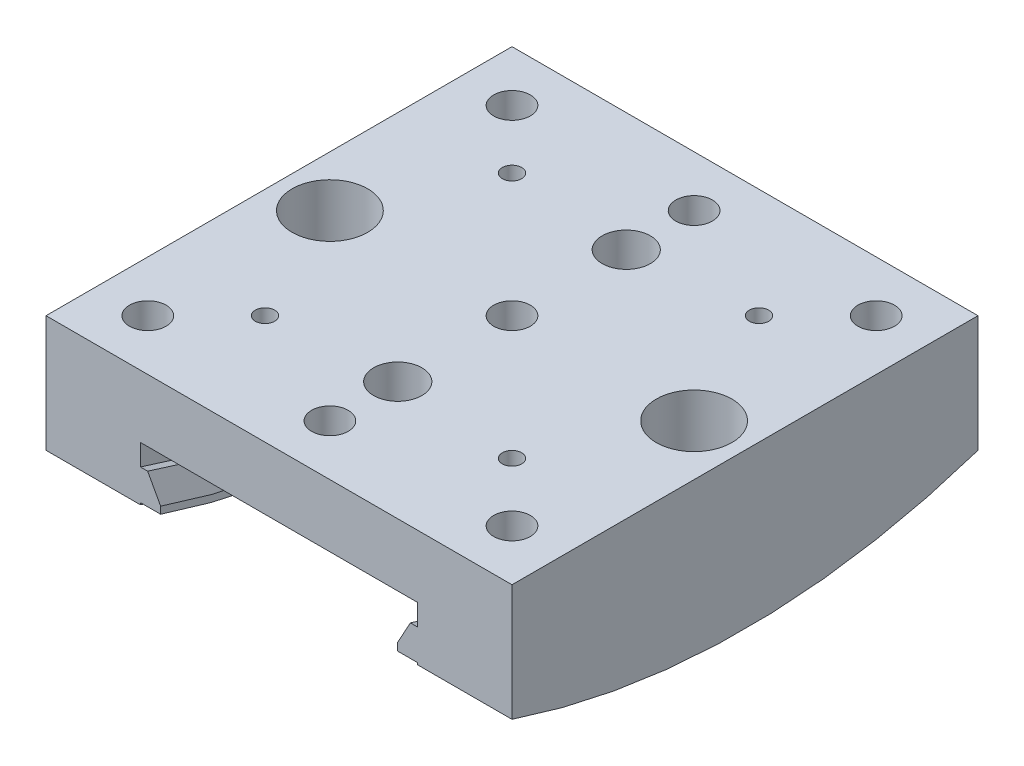
SolidWorks part; units mm, degrees
ref_plane "Ebene vorne" through (0, 0, 0) normal (0, 0, 1) x (1, 0, 0)
ref_plane "Ebene oben" through (0, 0, 0) normal (0, 1, 0) x (1, 0, 0)
ref_plane "Ebene rechts" through (0, 0, 0) normal (1, 0, 0) x (0, 0, -1)
sketch "Skizze1" plane through (0, 0, 0) normal (0, 0, 1) x (1, 0, 0)
  line L1 (-32.5, 15) -> (32.5, 15)
  line L2 (-32.5, 15) -> (-32.5, -15)
  line L3 (-32.5, -15) -> (32.5, -15)
  line L4 (32.5, 15) -> (32.5, -15)
  point P4 (0, 15)
  point P6 (-32.5, 0)
  dimension "D1" = 30
  dimension "D2" = 65
extrude "Aufsatz-Linear austragen1" add sketch "Skizze1" along normal blind 65
sketch "Skizze7" plane through (0, 0, 65) normal (0, 0, 1) x (1, 0, 0)
  line L0 (19.3305, 6.277) -> (-19.3305, 6.277)
  line L1 (-19.3305, 6.277) -> (-19.3305, 3.307)
  line L2 (-19.3305, 3.307) -> (-18.3215, 3.307)
  line L3 (-18.3215, 3.307) -> (-16.5095, -0.015)
  line L4 (-16.5095, -0.015) -> (-16.5095, -0.994)
  line L5 (-16.5095, -0.994) -> (-19.3305, -0.994)
  line L6 (-19.3305, -0.994) -> (-19.3305, -1.262)
  line L7 (-19.3305, -1.262) -> (19.3305, -1.262)
  line L9 (32.5, 15) -> (-32.5, 15) construction
  line L11 (19.3305, -0.994) -> (19.3305, -1.262)
  line L12 (16.5095, -0.994) -> (19.3305, -0.994)
  line L13 (16.5095, -0.015) -> (16.5095, -0.994)
  line L14 (18.3215, 3.307) -> (16.5095, -0.015)
  line L15 (19.3305, 3.307) -> (18.3215, 3.307)
  line L16 (19.3305, 6.277) -> (19.3305, 3.307)
  point P0 (0, 6.277)
  point P9 (0, 15)
  dimension "D1" = 2.97
  dimension "D2" = 1.009
  dimension "D3" = 0.979
  dimension "D4" = 38.661
  dimension "D5" = 8.723
  dimension "D6" = 2.821
  dimension "D7" = 0.268
  dimension "D8" = 16.262
sketch "Skizze8" plane through (0, 0, 0) normal (1, 0, 0) x (0, 0, -1)
  line L0 (-65, 15) -> (0, 15) construction
  circle A0 centre (-32.5, 95) radius 101.346
  point P4 (-32.5, 15)
  dimension "D1" = 202.692
  dimension "D2" = 80
sweep "Schnitt-Austragung2" cut profiles "Skizze7" path "Skizze8"
sketch "Skizze9" plane through (-32.5, 0, 0) normal (-1, 0, 0) x (0, 0, 1)
  line L0 (65, 15) -> (0, 15) construction
  line L3 (0, 15) -> (0, -15) construction
  line L5 (0, 15) -> (65, 15)
  line L6 (0, 15) -> (0, -15)
  line L7 (0, -15) -> (65, -15)
  line L8 (65, 15) -> (65, -15)
  circle A0 centre (32.5, 95) radius 101.6
  point P4 (32.5, 15)
  line M3 (0, -15) -> (65, -15)
  line M4 (65, -15) -> (65, 15)
  dimension "D1" = 203.2
  dimension "D2" = 80
extrude "Schnitt-Linear austragen2" cut sketch "Skizze9" against normal through all both and the other way through all contours A0 L6 M3 M4
sketch "Skizze10" plane through (0, 15, 0) normal (0, 1, 0) x (1, 0, 0)
  line L0 (-32.5, -65) -> (-32.5, 0) construction
  line L1 (0, -12.6224) -> (0, 12.6224) construction
  line L2 (-25.399, -32.5) -> (25.399, -32.5) construction
  line L3 (32.5, 0) -> (-32.5, 0) construction
  line L4 (0, -16.562) -> (0, -48.438) construction
  circle A0 centre (-25.399, -32.5) radius 5.2705
  circle A1 centre (25.399, -32.5) radius 5.2705
  circle A2 centre (0, -16.562) radius 3.3655
  circle A3 centre (0, -48.438) radius 3.3655
  circle A4 centre (-25.4, -7.1) radius 2.5525
  circle A6 centre (25.4, -7.1) radius 2.5525
  circle A10 centre (0, -7.1) radius 2.5525
  circle A11 centre (25.4, -57.9) radius 2.5525
  circle A12 centre (0, -57.9) radius 2.5525
  circle A13 centre (-25.4, -57.9) radius 2.5525
  circle A14 centre (-17.227, -15.273) radius 1.3525
  circle A15 centre (17.227, -15.273) radius 1.3525
  circle A16 centre (17.227, -49.727) radius 1.3525
  circle A17 centre (-17.227, -49.727) radius 1.3525
  circle A18 centre (0, -32.5) radius 2.5525
  point P4 (-32.5, -32.5)
  dimension "D1" = 10.541
  dimension "D3" = 6.731
  dimension "D5" = 5.105
  dimension "D8" = 2.705
  dimension "D11" = 5.105
  dimension "D2" = 7.101
  dimension "D4" = 16.562
  dimension "D6" = 7.1
  dimension "D7" = 7.1
  dimension "D9" = 15.273
  dimension "D10" = 15.273
extrude "Schnitt-Linear austragen4" cut sketch "Skizze10" against normal up to next
